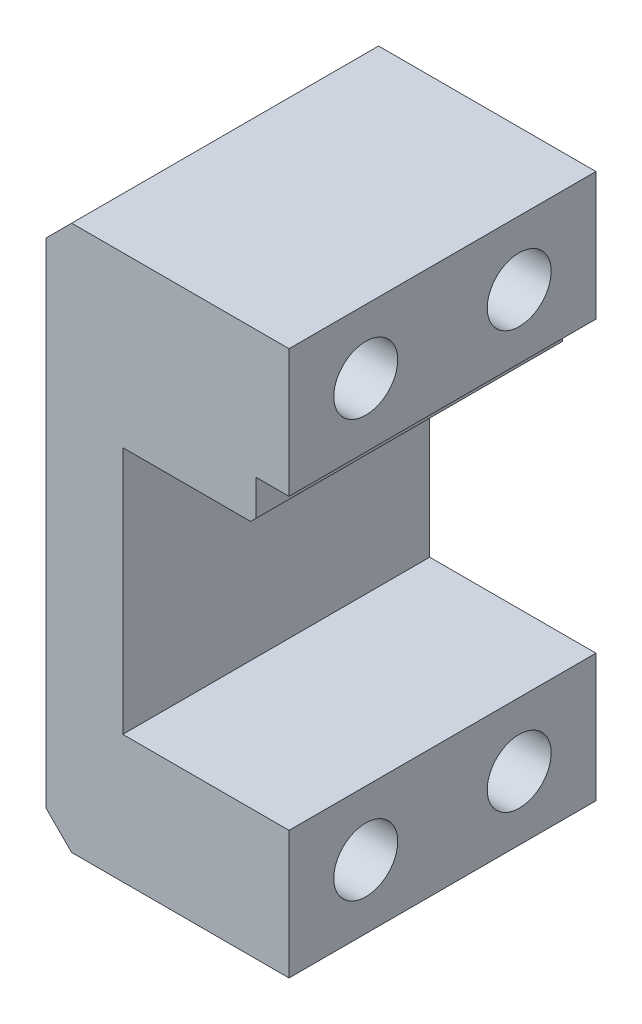
SolidWorks part; units mm, degrees
material "AISI 304"
ref_plane "前视基准面" through (0, 0, 0) normal (0, 0, 1) x (1, 0, 0)
ref_plane "上视基准面" through (0, 0, 0) normal (0, 1, 0) x (1, 0, 0)
ref_plane "右视基准面" through (0, 0, 0) normal (1, 0, 0) x (0, 0, -1)
sketch "草图1" plane through (0, 0, 0) normal (0, 0, 1) x (1, 0, 0)
  line L0 (0, 0) -> (0, 21.31)
  line L1 (0, 21.31) -> (9.5, 21.31)
  line L2 (9.5, 21.31) -> (9.5, 16.31)
  line L3 (9.5, 16.31) -> (8.2, 16.31)
  line L4 (8.2, 16.31) -> (8.2, 14.71)
  line L5 (8.2, 14.71) -> (3, 14.71)
  line L6 (3, 14.71) -> (3, 5)
  line L7 (3, 5) -> (9.5, 5)
  line L8 (9.5, 5) -> (9.5, 0)
  line L9 (9.5, 0) -> (0, 0)
  line L10 (9.5, 5) -> (9.5, 16.31) construction
  dimension "D1" = 5
  dimension "D2" = 9.71
  dimension "D3" = 3
  dimension "D4" = 1.3
  dimension "D5" = 6.5
  dimension "D6" = 1.6
  dimension "D7" = 5
extrude "凸台-拉伸1" add sketch "草图1" along normal blind 12
chamfer "倒角1" distance 0.2 angle 45 1 edges at (8.2, 14.71, 6)
sketch "草图2" plane through (0, 0, 0) normal (-1, 0, 0) x (0, 0, 1)
  line L0 (6, 21.31) -> (6, 0) construction
  line L1 (12, 21.31) -> (0, 21.31) construction
  line L2 (12, 0) -> (0, 0) construction
  line L3 (3, 18.81) -> (9, 18.81) construction
  line L4 (3, 2.5) -> (9, 2.5) construction
  line L5 (9, 2.5) -> (9, 18.81) construction
  line L6 (12, 21.31) -> (12, 0) construction
  circle A0 centre (9, 18.81) radius 1.5
  circle A1 centre (3, 18.81) radius 1.5
  circle A2 centre (3, 2.5) radius 1.5
  circle A3 centre (9, 2.5) radius 1.5
  point P9 (6, 18.81)
  point P12 (6, 2.5)
  dimension "D3" = 3
  dimension "D1" = 2.5
  dimension "D2" = 2.5
  dimension "D4" = 3
hole_wizard "M3 螺纹孔2" positions "3D草图3" profile "草图5" tap size "M3" standard "GB" end condition through all
sketch3d "3D草图3"
  point P0 (0, 2.5, 3)
  point P3 (0, 2.5, 9)
  point P6 (0, 18.81, 9)
  point P9 (0, 18.81, 3)
sketch "草图5" plane through (0, 2.5, 3) normal (0, 1, 0) x (0, 0, 1)
  line L0 (0, 0) -> (0, 9.5)
  line L1 (0, 9.5) -> (1.25, 9.5)
  line L2 (1.25, 9.5) -> (1.25, 0)
  line L5 (1.25, 0) -> (0, 0)
  line L11 (0, -6.35) -> (0, 107.95) construction
  dimension "通孔螺纹孔钻头直径" = 2.5
  dimension "通孔螺纹孔钻头深度" = 9.5
cosmetic thread "孔螺蚊线5" parameters "D2"=3
cosmetic thread "孔螺蚊线6" parameters "D2"=3
cosmetic thread "孔螺蚊线7" parameters "D2"=3
cosmetic thread "孔螺蚊线8" parameters "D2"=3
chamfer "倒角2" distance 1 angle 45 2 edges at (0, 0, 6) (0, 21.31, 6)
